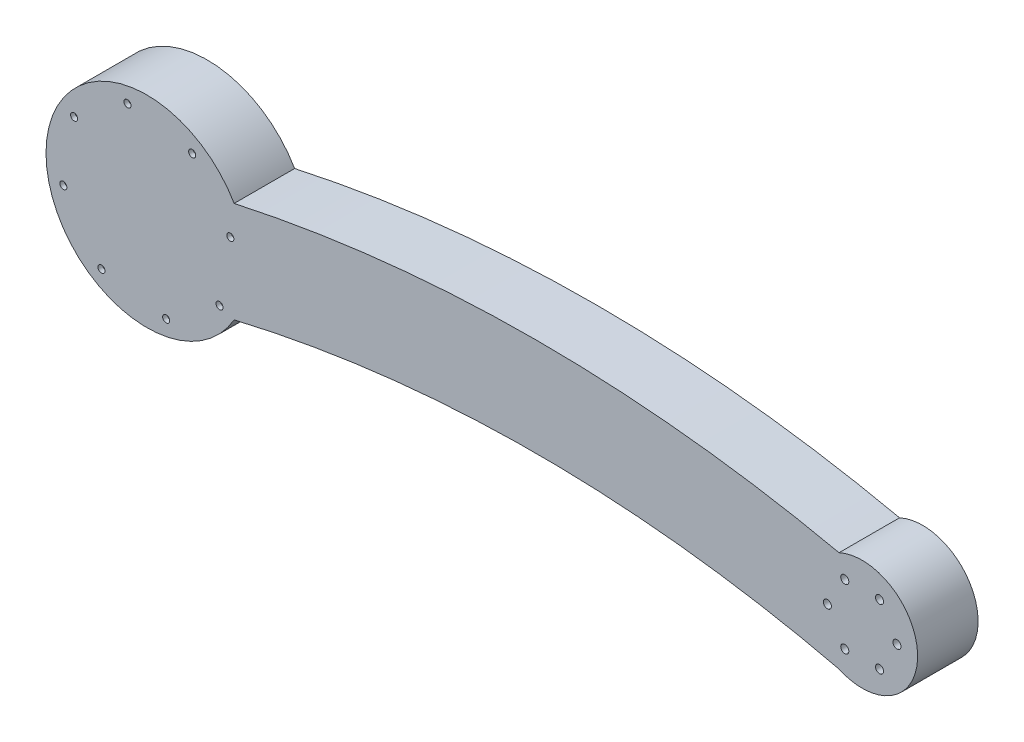
SolidWorks part; units mm, degrees
ref_plane "前视基准面" through (0, 0, 0) normal (0, 0, 1) x (1, 0, 0)
ref_plane "上视基准面" through (0, 0, 0) normal (0, 1, 0) x (1, 0, 0)
ref_plane "右视基准面" through (0, 0, 0) normal (1, 0, 0) x (0, 0, -1)
sketch "草图1" plane through (0, 0, 0) normal (0, 0, 1) x (1, 0, 0)
  line L1 (-150, 25) -> (150, 25)
  line L2 (-150, 25) -> (-150, -25)
  line L3 (-150, -25) -> (150, -25)
  line L4 (150, 25) -> (150, -25)
  line L5 (-150, 25) -> (150, -25) construction
  line L6 (-150, -25) -> (150, 25) construction
  arc A0 (-150, -25) -> (150, -25) centre (0, -657.4555) cw
  arc A1 (-150, 25) -> (150, 25) centre (0, -658.7397) cw
  circle A2 centre (161.4564, 0) radius 27.5
  circle A3 centre (-193.3013, 0) radius 50
  point P0 (0, 0)
  dimension "D3" = 50
  dimension "D4" = 650
  dimension "D5" = 700
  dimension "D6" = 55
  dimension "D7" = 100
  dimension "D1" = 300
  dimension "D2" = 50
extrude "凸台-拉伸3" add sketch "草图1" along normal blind 30 contours L4 A2 | L4 A2 | A3 A0 A2 L1 | A1 L1 | L2 A3 | L2 A3
sketch "草图3" plane through (0, 0, 0) normal (0, 0, -1) x (-1, 0, 0)
  line L0 (148.2429, 10.4311) -> (238.3596, -10.4311)
  line L1 (151.1094, 23.4074) -> (145.1153, -2.4848)
  line L2 (241.4602, 2.9624) -> (235.259, -23.8246)
  circle A0 centre (193.3013, 0) radius 48.25
  arc A4 (-150, 25) -> (-150, -25) centre (-161.4564, 0) ccw
  arc A5 (150, -25) -> (-150, -25) centre (0, -657.4555) ccw
  arc A6 (150, -25) -> (150, 25) centre (193.3013, 0) ccw
  arc A7 (150, 25) -> (-150, 25) centre (0, -658.7397) ccw
  arc A8 (-150, 25) -> (-150, -25) centre (-161.4564, 0) ccw
  arc A9 (150, -25) -> (-150, -25) centre (0, -657.4555) ccw
  arc A10 (150, -25) -> (150, 25) centre (193.3013, 0) ccw
  arc A11 (150, 25) -> (-150, 25) centre (0, -658.7397) ccw
  point P9 (193.3013, 0)
  point P16 (238.3596, -10.4311)
  dimension "D2" = 96.5
  dimension "D3" = 92.5
  dimension "D4" = 90.1167
  dimension "D5" = 25.8922
  dimension "D1" = 0
extrude "切除-拉伸1" cut sketch "草图3" against normal blind 27.75
sketch "草图5" plane through (0, 0, 27.75) normal (0, 0, -1) x (-1, 0, 0)
  line L0 (148.1123, 10.4613) -> (193.3013, 0) construction
  line L2 (235.259, -23.8246) -> (241.4602, 2.9624)
  line L3 (151.1094, 23.4074) -> (145.1153, -2.4848)
  line L4 (235.259, -23.8246) -> (241.4602, 2.9624)
  line L5 (151.1094, 23.4074) -> (145.1153, -2.4848)
  circle A0 centre (193.3013, 0) radius 42.5 construction
  circle A1 centre (151.8963, 9.5853) radius 1.75
  arc A2 (145.1153, -2.4848) -> (235.259, -23.8246) centre (193.3013, 0) ccw
  arc A3 (241.4602, 2.9624) -> (151.1094, 23.4074) centre (193.3013, 0) ccw
  arc A4 (145.1153, -2.4848) -> (235.259, -23.8246) centre (193.3013, 0) ccw
  arc A5 (241.4602, 2.9624) -> (151.1094, 23.4074) centre (193.3013, 0) ccw
  circle A6 centre (170.8014, 36.0556) radius 1.75
  circle A7 centre (202.8866, 41.405) radius 1.75
  circle A8 centre (229.3569, 22.4999) radius 1.75
  circle A9 centre (234.7062, -9.5853) radius 1.75
  circle A10 centre (215.8012, -36.0556) radius 1.75
  circle A11 centre (183.7159, -41.405) radius 1.75
  circle A12 centre (157.2457, -22.4999) radius 1.75
  point P27 (193.3013, 0)
  dimension "D2" = 85
  dimension "D3" = 3.5
  dimension "D1" = 0
  dimension "D4" = 8
extrude "切除-拉伸2" cut sketch "草图5" against normal through all contours A1 | A12 | A11 | A10 | A9 | A8 | A7 | A6
sketch "草图6" plane through (0, 0, 30) normal (0, 0, 1) x (1, 0, 0)
  circle A0 centre (161.4564, 0) radius 17.25 construction
  circle A1 centre (178.7064, 0) radius 2
  circle A2 centre (170.0814, -14.9389) radius 2
  circle A3 centre (152.8314, -14.9389) radius 2
  arc A4 (150, -25) -> (150, 25) centre (161.4564, 0) ccw
  arc A5 (150, 25) -> (-150, 25) centre (0, -658.7397) ccw
  arc A6 (-150, 25) -> (-150, -25) centre (-193.3013, 0) ccw
  arc A7 (150, -25) -> (-150, -25) centre (0, -657.4555) ccw
  arc A8 (150, -25) -> (150, 25) centre (161.4564, 0) ccw
  arc A9 (150, 25) -> (-150, 25) centre (0, -658.7397) ccw
  arc A10 (-150, 25) -> (-150, -25) centre (-193.3013, 0) ccw
  arc A11 (150, -25) -> (-150, -25) centre (0, -657.4555) ccw
  circle A12 centre (144.2064, 0) radius 2
  circle A13 centre (152.8314, 14.9389) radius 2
  circle A14 centre (170.0814, 14.9389) radius 2
  point P23 (161.4564, 0)
  dimension "D2" = 34.5
  dimension "D3" = 4
  dimension "D1" = 0
  dimension "D4" = 6
extrude "切除-拉伸3" cut sketch "草图6" against normal through all contours A13 | A12 | A14 | A1 | A2 | A3
